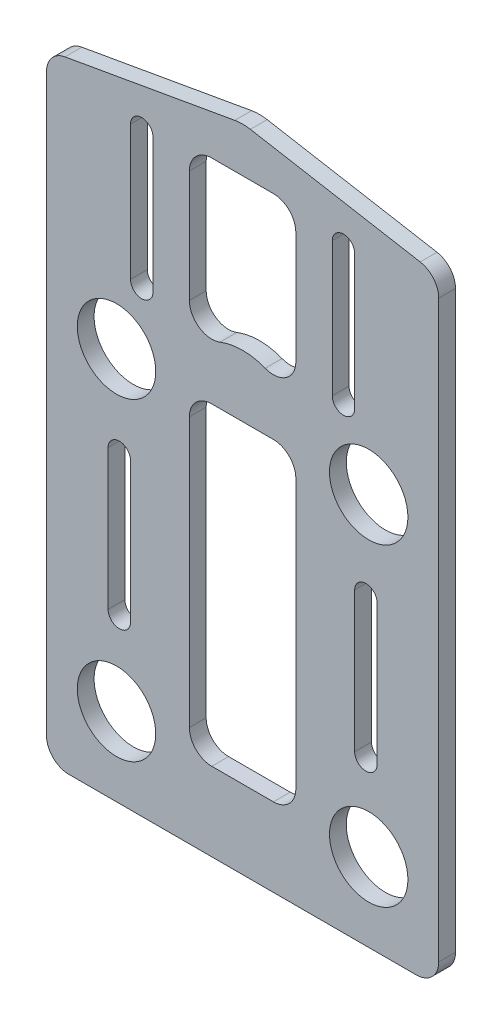
SolidWorks part; units mm, degrees
ref_plane "Alzado" through (0, 0, 0) normal (0, 0, 1) x (1, 0, 0)
ref_plane "Planta" through (0, 0, 0) normal (0, 1, 0) x (1, 0, 0)
ref_plane "Vista lateral" through (0, 0, 0) normal (1, 0, 0) x (0, 0, -1)
ref_plane "Plano1" through (0, 0, 0) normal (0, 0, -1) x (-1, 0, 0)
sketch "Croquis1" plane through (0, 0, 0) normal (0, 0, -1) x (-1, 0, 0)
  line L0 (-4.75, 14.512) -> (-4.75, 24.512)
  line L1 (-2.75, 26.512) -> (2.75, 26.512)
  line L2 (4.75, 24.512) -> (4.75, 14.512)
  line L3 (4.75, 5.512) -> (4.75, -18.488)
  line L4 (2.75, -20.488) -> (-2.75, -20.488)
  line L5 (-4.75, -18.488) -> (-4.75, 5.512)
  line L6 (-2.75, 7.512) -> (2.75, 7.512)
  line L7 (15.8473, 27.7794) -> (0.6946, 30.4512)
  line L8 (-0.6946, 30.4512) -> (-15.8473, 27.7794)
  line L9 (-17.5, 25.8098) -> (-17.5, -25.488)
  line L10 (-15.5, -27.488) -> (15.5, -27.488)
  line L11 (17.5, -25.488) -> (17.5, 25.8098)
  line L12 (12, -0.488) -> (12, -12.988)
  line L13 (10, -12.988) -> (10, -0.488)
  line L14 (10, 25.512) -> (10, 13.512)
  line L15 (8, 13.512) -> (8, 25.512)
  line L16 (-10, -0.488) -> (-10, -12.988)
  line L17 (-12, -12.988) -> (-12, -0.488)
  line L18 (-8, 25.512) -> (-8, 13.512)
  line L19 (-10, 13.512) -> (-10, 25.512)
  arc A0 (2.0177, 12.6509) -> (-2.0177, 12.6509) centre (0, 7.5228) ccw
  arc A1 (-2.0177, 12.6509) -> (-4.75, 14.512) centre (-2.75, 14.512) cw
  arc A2 (-4.75, 24.512) -> (-2.75, 26.512) centre (-2.75, 24.512) cw
  arc A3 (2.75, 26.512) -> (4.75, 24.512) centre (2.75, 24.512) cw
  arc A4 (4.75, 14.512) -> (2.0177, 12.6509) centre (2.75, 14.512) cw
  arc A5 (4.75, -18.488) -> (2.75, -20.488) centre (2.75, -18.488) cw
  arc A6 (-2.75, -20.488) -> (-4.75, -18.488) centre (-2.75, -18.488) cw
  arc A7 (-4.75, 5.512) -> (-2.75, 7.512) centre (-2.75, 5.512) cw
  arc A8 (2.75, 7.512) -> (4.75, 5.512) centre (2.75, 5.512) cw
  arc A9 (17.5, 25.8098) -> (15.8473, 27.7794) centre (15.5, 25.8098) ccw
  arc A10 (0.6946, 30.4512) -> (-0.6946, 30.4512) centre (0, 26.512) ccw
  arc A11 (-15.8473, 27.7794) -> (-17.5, 25.8098) centre (-15.5, 25.8098) ccw
  arc A12 (-17.5, -25.488) -> (-15.5, -27.488) centre (-15.5, -25.488) ccw
  arc A13 (15.5, -27.488) -> (17.5, -25.488) centre (15.5, -25.488) ccw
  circle A14 centre (11.25, 7.512) radius 3.5
  circle A15 centre (11.25, -20.488) radius 3.5
  circle A16 centre (-11.25, -20.488) radius 3.5
  circle A17 centre (-11.25, 7.512) radius 3.5
  arc A18 (10, -0.488) -> (12, -0.488) centre (11, -0.488) cw
  arc A19 (12, -12.988) -> (10, -12.988) centre (11, -12.988) cw
  arc A20 (8, 25.512) -> (10, 25.512) centre (9, 25.512) cw
  arc A21 (10, 13.512) -> (8, 13.512) centre (9, 13.512) cw
  arc A22 (-12, -0.488) -> (-10, -0.488) centre (-11, -0.488) cw
  arc A23 (-10, -12.988) -> (-12, -12.988) centre (-11, -12.988) cw
  arc A24 (-10, 25.512) -> (-8, 25.512) centre (-9, 25.512) cw
  arc A25 (-8, 13.512) -> (-10, 13.512) centre (-9, 13.512) cw
extrude "Saliente-Extruir1" add sketch "Croquis1" against normal blind 1.5
